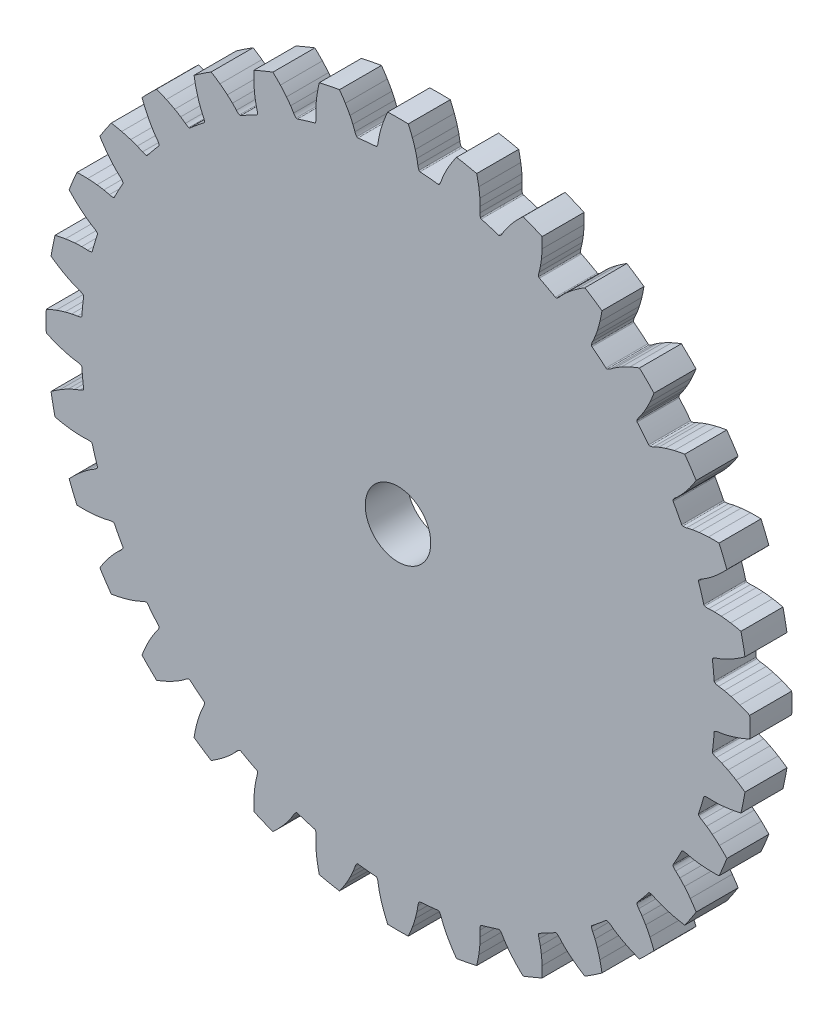
SolidWorks part; units mm, degrees
material "ASTM A36 Steel"
ref_plane "Front Plane" through (0, 0, 0) normal (0, 0, 1) x (1, 0, 0)
ref_plane "Top Plane" through (0, 0, 0) normal (0, 1, 0) x (1, 0, 0)
ref_plane "Right Plane" through (0, 0, 0) normal (1, 0, 0) x (0, 0, -1)
sketch "Model" plane through (0, 0, 0) normal (0, 0, 1) x (1, 0, 0)
  arc A1 (47.6887, -4.6969) -> (47.803, -3.3385) centre (0, 0) ccw
  arc A2 (47.9144, -3.1714) -> (47.803, -3.3385) centre (48.0052, -3.3526) ccw
  arc A3 (48.4758, -3.0015) -> (47.9144, -3.1714) centre (48.6888, -4.7173) ccw
  arc A4 (48.4758, -3.0015) -> (49.3301, -2.859) centre (47.1969, 7.2969) ccw
  arc A5 (49.3301, -2.859) -> (50.3502, -2.6078) centre (46.1914, 12.0843) ccw
  arc A6 (50.3502, -2.6078) -> (51.6994, -2.1663) centre (45.5635, 14.3022) ccw
  arc A7 (51.6994, -2.1663) -> (53.1817, -1.5528) centre (43.8651, 18.8607) ccw
  arc A8 (53.1817, -1.5528) -> (53.1817, 1.5528) centre (0, 0) ccw
  arc A9 (53.1817, 1.5528) -> (51.6994, 2.1663) centre (43.8651, -18.8607) ccw
  arc A10 (51.6994, 2.1663) -> (50.3502, 2.6078) centre (45.5635, -14.3022) ccw
  arc A11 (50.3502, 2.6078) -> (49.3301, 2.859) centre (46.1914, -12.0843) ccw
  arc A12 (49.3301, 2.859) -> (48.4758, 3.0015) centre (47.1969, -7.2969) ccw
  arc A13 (47.9144, 3.1714) -> (48.4758, 3.0015) centre (48.6888, 4.7173) ccw
  arc A14 (47.803, 3.3385) -> (47.9144, 3.1714) centre (48.0052, 3.3526) ccw
  arc A15 (47.803, 3.3385) -> (47.5358, 6.0515) centre (0, 0) ccw
  arc A16 (47.6124, 6.2371) -> (47.5358, 6.0515) centre (47.7368, 6.0771) ccw
  arc A17 (48.1299, 6.5133) -> (47.6124, 6.2371) centre (48.6736, 4.872) ccw
  arc A18 (48.1299, 6.5133) -> (48.94, 6.8198) centre (44.8665, 16.3643) ccw
  arc A19 (48.94, 6.8198) -> (49.8915, 7.2652) centre (42.9463, 20.8636) ccw
  arc A20 (49.8915, 7.2652) -> (51.1287, 7.9614) centre (41.8978, 22.9164) ccw
  arc A21 (51.1287, 7.9614) -> (52.4627, 8.8522) centre (39.3427, 27.056) ccw
  arc A22 (52.4627, 8.8522) -> (51.8568, 11.8982) centre (0, 0) ccw
  arc A23 (51.8568, 11.8982) -> (50.2834, 12.2107) centre (46.7018, -9.9407) ccw
  arc A24 (50.2834, 12.2107) -> (48.874, 12.3805) centre (47.4783, -5.1384) ccw
  arc A25 (48.874, 12.3805) -> (47.8244, 12.4279) centre (47.6613, -2.8406) ccw
  arc A26 (47.8244, 12.4279) -> (46.9587, 12.401) centre (47.7136, 2.051) ccw
  arc A27 (46.375, 12.4581) -> (46.9587, 12.401) centre (46.833, 14.1254) ccw
  arc A28 (46.2332, 12.6003) -> (46.375, 12.4581) centre (46.4287, 12.6536) ccw
  arc A29 (46.2332, 12.6003) -> (45.4418, 15.209) centre (0, 0) ccw
  arc A30 (45.4808, 15.406) -> (45.4418, 15.209) centre (45.634, 15.2733) ccw
  arc A31 (45.9344, 15.7779) -> (45.4808, 15.406) centre (46.7879, 14.2741) ccw
  arc A32 (45.9344, 15.7779) -> (46.6691, 16.2364) centre (40.8119, 24.8029) ccw
  arc A33 (46.6691, 16.2364) -> (47.5155, 16.8589) centre (38.0508, 28.8411) ccw
  arc A34 (47.5155, 16.8589) -> (48.5931, 17.7832) centre (36.622, 30.6499) ccw
  arc A35 (48.5931, 17.7832) -> (49.7277, 18.9171) centre (33.3084, 34.2115) ccw
  arc A36 (49.7277, 18.9171) -> (48.5392, 21.7864) centre (0, 0) ccw
  arc A37 (48.5392, 21.7864) -> (46.9351, 21.7859) centre (47.7438, -0.6386) ccw
  arc A38 (46.9351, 21.7859) -> (45.5196, 21.6775) centre (47.5684, 4.2229) ccw
  arc A39 (45.5196, 21.6775) -> (44.481, 21.5192) centre (47.2997, 6.5122) ccw
  arc A40 (44.481, 21.5192) -> (43.6371, 21.3239) centre (46.3967, 11.3201) ccw
  arc A41 (43.0535, 21.2661) -> (43.6371, 21.3239) centre (43.1774, 22.9907) ccw
  arc A42 (42.8866, 21.3778) -> (43.0535, 21.2661) centre (43.068, 21.4682) ccw
  arc A43 (42.8866, 21.3778) -> (41.6015, 23.782) centre (0, 0) ccw
  arc A44 (41.6013, 23.9828) -> (41.6015, 23.782) centre (41.7775, 23.8826) ccw
  arc A45 (41.9737, 24.436) -> (41.6013, 23.9828) centre (43.1041, 23.1277) ccw
  arc A46 (41.9737, 24.436) -> (42.6048, 25.0292) centre (35.1889, 32.2883) ccw
  arc A47 (42.6048, 25.0292) -> (43.3135, 25.8048) centre (31.693, 35.7103) ccw
  arc A48 (43.3135, 25.8048) -> (44.19, 26.9215) centre (29.9388, 37.2056) ccw
  arc A49 (44.19, 26.9215) -> (45.0816, 28.255) centre (25.994, 40.0523) ccw
  arc A50 (45.0816, 28.255) -> (43.3562, 30.8373) centre (0, 0) ccw
  arc A51 (43.3562, 30.8373) -> (41.783, 30.5239) centre (46.951, 8.688) ccw
  arc A52 (41.783, 30.5239) -> (40.4159, 30.1414) centre (45.8306, 13.4219) ccw
  arc A53 (40.4159, 30.1414) -> (39.4281, 29.7835) centre (45.1204, 15.6148) ccw
  arc A54 (39.4281, 29.7835) -> (38.6386, 29.4273) centre (43.2967, 20.1541) ccw
  arc A55 (38.0774, 29.2568) -> (38.6386, 29.4273) centre (37.8625, 30.9724) ccw
  arc A56 (37.892, 29.3338) -> (38.0774, 29.2568) centre (38.0522, 29.4579) ccw
  arc A57 (37.892, 29.3338) -> (36.1625, 31.4411) centre (0, 0) ccw
  arc A58 (36.1231, 31.638) -> (36.1625, 31.4411) centre (36.3154, 31.5741) ccw
  arc A59 (36.3999, 32.1552) -> (36.1231, 31.638) centre (37.7639, 31.0925) ccw
  arc A60 (36.3999, 32.1552) -> (36.9032, 32.86) centre (28.2136, 38.5329) ccw
  arc A61 (36.9032, 32.86) -> (37.447, 33.759) centre (24.1173, 41.2071) ccw
  arc A62 (37.447, 33.759) -> (38.0888, 35.0253) centre (22.1051, 42.3315) ccw
  arc A63 (38.0888, 35.0253) -> (38.7031, 36.5071) centre (17.6808, 44.3539) ccw
  arc A64 (38.7031, 36.5071) -> (36.5071, 38.7031) centre (0, 0) ccw
  arc A65 (36.5071, 38.7031) -> (35.0253, 38.0888) centre (44.3539, 17.6808) ccw
  arc A66 (35.0253, 38.0888) -> (33.759, 37.447) centre (42.3315, 22.1051) ccw
  arc A67 (33.759, 37.447) -> (32.86, 36.9032) centre (41.2071, 24.1173) ccw
  arc A68 (32.86, 36.9032) -> (32.1552, 36.3999) centre (38.5329, 28.2136) ccw
  arc A69 (31.638, 36.1231) -> (32.1552, 36.3999) centre (31.0925, 37.7639) ccw
  arc A70 (31.4411, 36.1625) -> (31.638, 36.1231) centre (31.5741, 36.3154) ccw
  arc A71 (31.4411, 36.1625) -> (29.3338, 37.892) centre (0, 0) ccw
  arc A72 (29.2568, 38.0774) -> (29.3338, 37.892) centre (29.4579, 38.0522) ccw
  arc A73 (29.4273, 38.6386) -> (29.2568, 38.0774) centre (30.9724, 37.8625) ccw
  arc A74 (29.4273, 38.6386) -> (29.7835, 39.4281) centre (20.1541, 43.2967) ccw
  arc A75 (29.7835, 39.4281) -> (30.1414, 40.4159) centre (15.6148, 45.1204) ccw
  arc A76 (30.1414, 40.4159) -> (30.5239, 41.783) centre (13.4219, 45.8306) ccw
  arc A77 (30.5239, 41.783) -> (30.8373, 43.3562) centre (8.688, 46.951) ccw
  arc A78 (30.8373, 43.3562) -> (28.255, 45.0816) centre (0, 0) ccw
  arc A79 (28.255, 45.0816) -> (26.9215, 44.19) centre (40.0523, 25.994) ccw
  arc A80 (26.9215, 44.19) -> (25.8048, 43.3135) centre (37.2056, 29.9388) ccw
  arc A81 (25.8048, 43.3135) -> (25.0292, 42.6048) centre (35.7103, 31.693) ccw
  arc A82 (25.0292, 42.6048) -> (24.436, 41.9737) centre (32.2883, 35.1889) ccw
  arc A83 (23.9828, 41.6013) -> (24.436, 41.9737) centre (23.1277, 43.1041) ccw
  arc A84 (23.782, 41.6015) -> (23.9828, 41.6013) centre (23.8826, 41.7775) ccw
  arc A85 (23.782, 41.6015) -> (21.3778, 42.8866) centre (0, 0) ccw
  arc A86 (21.2661, 43.0535) -> (21.3778, 42.8866) centre (21.4682, 43.068) ccw
  arc A87 (21.3239, 43.6371) -> (21.2661, 43.0535) centre (22.9907, 43.1774) ccw
  arc A88 (21.3239, 43.6371) -> (21.5192, 44.481) centre (11.3201, 46.3967) ccw
  arc A89 (21.5192, 44.481) -> (21.6775, 45.5196) centre (6.5122, 47.2997) ccw
  arc A90 (21.6775, 45.5196) -> (21.7859, 46.9351) centre (4.2229, 47.5684) ccw
  arc A91 (21.7859, 46.9351) -> (21.7864, 48.5392) centre (-0.6386, 47.7438) ccw
  arc A92 (21.7864, 48.5392) -> (18.9171, 49.7277) centre (0, 0) ccw
  arc A93 (18.9171, 49.7277) -> (17.7832, 48.5931) centre (34.2115, 33.3084) ccw
  arc A94 (17.7832, 48.5931) -> (16.8589, 47.5155) centre (30.6499, 36.622) ccw
  arc A95 (16.8589, 47.5155) -> (16.2364, 46.6691) centre (28.8411, 38.0508) ccw
  arc A96 (16.2364, 46.6691) -> (15.7779, 45.9344) centre (24.8029, 40.8119) ccw
  arc A97 (15.406, 45.4808) -> (15.7779, 45.9344) centre (14.2741, 46.7879) ccw
  arc A98 (15.209, 45.4418) -> (15.406, 45.4808) centre (15.2733, 45.634) ccw
  arc A99 (15.209, 45.4418) -> (12.6003, 46.2332) centre (0, 0) ccw
  arc A100 (12.4581, 46.375) -> (12.6003, 46.2332) centre (12.6536, 46.4287) ccw
  arc A101 (12.401, 46.9587) -> (12.4581, 46.375) centre (14.1254, 46.833) ccw
  arc A102 (12.401, 46.9587) -> (12.4279, 47.8244) centre (2.051, 47.7136) ccw
  arc A103 (12.4279, 47.8244) -> (12.3805, 48.874) centre (-2.8406, 47.6613) ccw
  arc A104 (12.3805, 48.874) -> (12.2107, 50.2834) centre (-5.1384, 47.4783) ccw
  arc A105 (12.2107, 50.2834) -> (11.8982, 51.8568) centre (-9.9407, 46.7018) ccw
  arc A106 (11.8982, 51.8568) -> (8.8522, 52.4627) centre (0, 0) ccw
  arc A107 (8.8522, 52.4627) -> (7.9614, 51.1287) centre (27.056, 39.3427) ccw
  arc A108 (7.9614, 51.1287) -> (7.2652, 49.8915) centre (22.9164, 41.8978) ccw
  arc A109 (7.2652, 49.8915) -> (6.8198, 48.94) centre (20.8636, 42.9463) ccw
  arc A110 (6.8198, 48.94) -> (6.5133, 48.1299) centre (16.3643, 44.8665) ccw
  arc A111 (6.2371, 47.6124) -> (6.5133, 48.1299) centre (4.872, 48.6736) ccw
  arc A112 (6.0515, 47.5358) -> (6.2371, 47.6124) centre (6.0771, 47.7368) ccw
  arc A113 (6.0515, 47.5358) -> (3.3385, 47.803) centre (0, 0) ccw
  arc A114 (3.1714, 47.9144) -> (3.3385, 47.803) centre (3.3526, 48.0052) ccw
  arc A115 (3.0015, 48.4758) -> (3.1714, 47.9144) centre (4.7173, 48.6888) ccw
  arc A116 (3.0015, 48.4758) -> (2.859, 49.3301) centre (-7.2969, 47.1969) ccw
  arc A117 (2.859, 49.3301) -> (2.6078, 50.3502) centre (-12.0843, 46.1914) ccw
  arc A118 (2.6078, 50.3502) -> (2.1663, 51.6994) centre (-14.3022, 45.5635) ccw
  arc A119 (2.1663, 51.6994) -> (1.5528, 53.1817) centre (-18.8607, 43.8651) ccw
  arc A120 (1.5528, 53.1817) -> (-1.5528, 53.1817) centre (0, 0) ccw
  arc A121 (-1.5528, 53.1817) -> (-2.1663, 51.6994) centre (18.8607, 43.8651) ccw
  arc A122 (-2.1663, 51.6994) -> (-2.6078, 50.3502) centre (14.3022, 45.5635) ccw
  arc A123 (-2.6078, 50.3502) -> (-2.859, 49.3301) centre (12.0843, 46.1914) ccw
  arc A124 (-2.859, 49.3301) -> (-3.0015, 48.4758) centre (7.2969, 47.1969) ccw
  arc A125 (-3.1714, 47.9144) -> (-3.0015, 48.4758) centre (-4.7173, 48.6888) ccw
  arc A126 (-3.3385, 47.803) -> (-3.1714, 47.9144) centre (-3.3526, 48.0052) ccw
  arc A127 (-3.3385, 47.803) -> (-6.0515, 47.5358) centre (0, 0) ccw
  arc A128 (-6.2371, 47.6124) -> (-6.0515, 47.5358) centre (-6.0771, 47.7368) ccw
  arc A129 (-6.5133, 48.1299) -> (-6.2371, 47.6124) centre (-4.872, 48.6736) ccw
  arc A130 (-6.5133, 48.1299) -> (-6.8198, 48.94) centre (-16.3643, 44.8665) ccw
  arc A131 (-6.8198, 48.94) -> (-7.2652, 49.8915) centre (-20.8636, 42.9463) ccw
  arc A132 (-7.2652, 49.8915) -> (-7.9614, 51.1287) centre (-22.9164, 41.8978) ccw
  arc A133 (-7.9614, 51.1287) -> (-8.8522, 52.4627) centre (-27.056, 39.3427) ccw
  arc A134 (-8.8522, 52.4627) -> (-11.8982, 51.8568) centre (0, 0) ccw
  arc A135 (-11.8982, 51.8568) -> (-12.2107, 50.2834) centre (9.9407, 46.7018) ccw
  arc A136 (-12.2107, 50.2834) -> (-12.3805, 48.874) centre (5.1384, 47.4783) ccw
  arc A137 (-12.3805, 48.874) -> (-12.4279, 47.8244) centre (2.8406, 47.6613) ccw
  arc A138 (-12.4279, 47.8244) -> (-12.401, 46.9587) centre (-2.051, 47.7136) ccw
  arc A139 (-12.4581, 46.375) -> (-12.401, 46.9587) centre (-14.1254, 46.833) ccw
  arc A140 (-12.6003, 46.2332) -> (-12.4581, 46.375) centre (-12.6536, 46.4287) ccw
  arc A141 (-12.6003, 46.2332) -> (-15.209, 45.4418) centre (0, 0) ccw
  arc A142 (-15.406, 45.4808) -> (-15.209, 45.4418) centre (-15.2733, 45.634) ccw
  arc A143 (-15.7779, 45.9344) -> (-15.406, 45.4808) centre (-14.2741, 46.7879) ccw
  arc A144 (-15.7779, 45.9344) -> (-16.2364, 46.6691) centre (-24.8029, 40.8119) ccw
  arc A145 (-16.2364, 46.6691) -> (-16.8589, 47.5155) centre (-28.8411, 38.0508) ccw
  arc A146 (-16.8589, 47.5155) -> (-17.7832, 48.5931) centre (-30.6499, 36.622) ccw
  arc A147 (-17.7832, 48.5931) -> (-18.9171, 49.7277) centre (-34.2115, 33.3084) ccw
  arc A148 (-18.9171, 49.7277) -> (-21.7864, 48.5392) centre (0, 0) ccw
  arc A149 (-21.7864, 48.5392) -> (-21.7859, 46.9351) centre (0.6386, 47.7438) ccw
  arc A150 (-21.7859, 46.9351) -> (-21.6775, 45.5196) centre (-4.2229, 47.5684) ccw
  arc A151 (-21.6775, 45.5196) -> (-21.5192, 44.481) centre (-6.5122, 47.2997) ccw
  arc A152 (-21.5192, 44.481) -> (-21.3239, 43.6371) centre (-11.3201, 46.3967) ccw
  arc A153 (-21.2661, 43.0535) -> (-21.3239, 43.6371) centre (-22.9907, 43.1774) ccw
  arc A154 (-21.3778, 42.8866) -> (-21.2661, 43.0535) centre (-21.4682, 43.068) ccw
  arc A155 (-21.3778, 42.8866) -> (-23.782, 41.6015) centre (0, 0) ccw
  arc A156 (-23.9828, 41.6013) -> (-23.782, 41.6015) centre (-23.8826, 41.7775) ccw
  arc A157 (-24.436, 41.9737) -> (-23.9828, 41.6013) centre (-23.1277, 43.1041) ccw
  arc A158 (-24.436, 41.9737) -> (-25.0292, 42.6048) centre (-32.2883, 35.1889) ccw
  arc A159 (-25.0292, 42.6048) -> (-25.8048, 43.3135) centre (-35.7103, 31.693) ccw
  arc A160 (-25.8048, 43.3135) -> (-26.9215, 44.19) centre (-37.2056, 29.9388) ccw
  arc A161 (-26.9215, 44.19) -> (-28.255, 45.0816) centre (-40.0523, 25.994) ccw
  arc A162 (-28.255, 45.0816) -> (-30.8373, 43.3562) centre (0, 0) ccw
  arc A163 (-30.8373, 43.3562) -> (-30.5239, 41.783) centre (-8.688, 46.951) ccw
  arc A164 (-30.5239, 41.783) -> (-30.1414, 40.4159) centre (-13.4219, 45.8306) ccw
  arc A165 (-30.1414, 40.4159) -> (-29.7835, 39.4281) centre (-15.6148, 45.1204) ccw
  arc A166 (-29.7835, 39.4281) -> (-29.4273, 38.6386) centre (-20.1541, 43.2967) ccw
  arc A167 (-29.2568, 38.0774) -> (-29.4273, 38.6386) centre (-30.9724, 37.8625) ccw
  arc A168 (-29.3338, 37.892) -> (-29.2568, 38.0774) centre (-29.4579, 38.0522) ccw
  arc A169 (-29.3338, 37.892) -> (-31.4411, 36.1625) centre (0, 0) ccw
  arc A170 (-31.638, 36.1231) -> (-31.4411, 36.1625) centre (-31.5741, 36.3154) ccw
  arc A171 (-32.1552, 36.3999) -> (-31.638, 36.1231) centre (-31.0925, 37.7639) ccw
  arc A172 (-32.1552, 36.3999) -> (-32.86, 36.9032) centre (-38.5329, 28.2136) ccw
  arc A173 (-32.86, 36.9032) -> (-33.759, 37.447) centre (-41.2071, 24.1173) ccw
  arc A174 (-33.759, 37.447) -> (-35.0253, 38.0888) centre (-42.3315, 22.1051) ccw
  arc A175 (-35.0253, 38.0888) -> (-36.5071, 38.7031) centre (-44.3539, 17.6808) ccw
  arc A176 (-36.5071, 38.7031) -> (-38.7031, 36.5071) centre (0, 0) ccw
  arc A177 (-38.7031, 36.5071) -> (-38.0888, 35.0253) centre (-17.6808, 44.3539) ccw
  arc A178 (-38.0888, 35.0253) -> (-37.447, 33.759) centre (-22.1051, 42.3315) ccw
  arc A179 (-37.447, 33.759) -> (-36.9032, 32.86) centre (-24.1173, 41.2071) ccw
  arc A180 (-36.9032, 32.86) -> (-36.3999, 32.1552) centre (-28.2136, 38.5329) ccw
  arc A181 (-36.1231, 31.638) -> (-36.3999, 32.1552) centre (-37.7639, 31.0925) ccw
  arc A182 (-36.1625, 31.4411) -> (-36.1231, 31.638) centre (-36.3154, 31.5741) ccw
  arc A183 (-36.1625, 31.4411) -> (-37.892, 29.3338) centre (0, 0) ccw
  arc A184 (-38.0774, 29.2568) -> (-37.892, 29.3338) centre (-38.0522, 29.4579) ccw
  arc A185 (-38.6386, 29.4273) -> (-38.0774, 29.2568) centre (-37.8625, 30.9724) ccw
  arc A186 (-38.6386, 29.4273) -> (-39.4281, 29.7835) centre (-43.2967, 20.1541) ccw
  arc A187 (-39.4281, 29.7835) -> (-40.4159, 30.1414) centre (-45.1204, 15.6148) ccw
  arc A188 (-40.4159, 30.1414) -> (-41.783, 30.5239) centre (-45.8306, 13.4219) ccw
  arc A189 (-41.783, 30.5239) -> (-43.3562, 30.8373) centre (-46.951, 8.688) ccw
  arc A190 (-43.3562, 30.8373) -> (-45.0816, 28.255) centre (0, 0) ccw
  arc A191 (-45.0816, 28.255) -> (-44.19, 26.9215) centre (-25.994, 40.0523) ccw
  arc A192 (-44.19, 26.9215) -> (-43.3135, 25.8048) centre (-29.9388, 37.2056) ccw
  arc A193 (-43.3135, 25.8048) -> (-42.6048, 25.0292) centre (-31.693, 35.7103) ccw
  arc A194 (-42.6048, 25.0292) -> (-41.9737, 24.436) centre (-35.1889, 32.2883) ccw
  arc A195 (-41.6013, 23.9828) -> (-41.9737, 24.436) centre (-43.1041, 23.1277) ccw
  arc A196 (-41.6015, 23.782) -> (-41.6013, 23.9828) centre (-41.7775, 23.8826) ccw
  arc A197 (-41.6015, 23.782) -> (-42.8866, 21.3778) centre (0, 0) ccw
  arc A198 (-43.0535, 21.2661) -> (-42.8866, 21.3778) centre (-43.068, 21.4682) ccw
  arc A199 (-43.6371, 21.3239) -> (-43.0535, 21.2661) centre (-43.1774, 22.9907) ccw
  arc A200 (-43.6371, 21.3239) -> (-44.481, 21.5192) centre (-46.3967, 11.3201) ccw
  arc A201 (-44.481, 21.5192) -> (-45.5196, 21.6775) centre (-47.2997, 6.5122) ccw
  arc A202 (-45.5196, 21.6775) -> (-46.9351, 21.7859) centre (-47.5684, 4.2229) ccw
  arc A203 (-46.9351, 21.7859) -> (-48.5392, 21.7864) centre (-47.7438, -0.6386) ccw
  arc A204 (-48.5392, 21.7864) -> (-49.7277, 18.9171) centre (0, 0) ccw
  arc A205 (-49.7277, 18.9171) -> (-48.5931, 17.7832) centre (-33.3084, 34.2115) ccw
  arc A206 (-48.5931, 17.7832) -> (-47.5155, 16.8589) centre (-36.622, 30.6499) ccw
  arc A207 (-47.5155, 16.8589) -> (-46.6691, 16.2364) centre (-38.0508, 28.8411) ccw
  arc A208 (-46.6691, 16.2364) -> (-45.9344, 15.7779) centre (-40.8119, 24.8029) ccw
  arc A209 (-45.4808, 15.406) -> (-45.9344, 15.7779) centre (-46.7879, 14.2741) ccw
  arc A210 (-45.4418, 15.209) -> (-45.4808, 15.406) centre (-45.634, 15.2733) ccw
  arc A211 (-45.4418, 15.209) -> (-46.2332, 12.6003) centre (0, 0) ccw
  arc A212 (-46.375, 12.4581) -> (-46.2332, 12.6003) centre (-46.4287, 12.6536) ccw
  arc A213 (-46.9587, 12.401) -> (-46.375, 12.4581) centre (-46.833, 14.1254) ccw
  arc A214 (-46.9587, 12.401) -> (-47.8244, 12.4279) centre (-47.7136, 2.051) ccw
  arc A215 (-47.8244, 12.4279) -> (-48.874, 12.3805) centre (-47.6613, -2.8406) ccw
  arc A216 (-48.874, 12.3805) -> (-50.2834, 12.2107) centre (-47.4783, -5.1384) ccw
  arc A217 (-50.2834, 12.2107) -> (-51.8568, 11.8982) centre (-46.7018, -9.9407) ccw
  arc A218 (-51.8568, 11.8982) -> (-52.4627, 8.8522) centre (0, 0) ccw
  arc A219 (-52.4627, 8.8522) -> (-51.1287, 7.9614) centre (-39.3427, 27.056) ccw
  arc A220 (-51.1287, 7.9614) -> (-49.8915, 7.2652) centre (-41.8978, 22.9164) ccw
  arc A221 (-49.8915, 7.2652) -> (-48.94, 6.8198) centre (-42.9463, 20.8636) ccw
  arc A222 (-48.94, 6.8198) -> (-48.1299, 6.5133) centre (-44.8665, 16.3643) ccw
  arc A223 (-47.6124, 6.2371) -> (-48.1299, 6.5133) centre (-48.6736, 4.872) ccw
  arc A224 (-47.5358, 6.0515) -> (-47.6124, 6.2371) centre (-47.7368, 6.0771) ccw
  arc A225 (-47.5358, 6.0515) -> (-47.803, 3.3385) centre (0, 0) ccw
  arc A226 (-47.9144, 3.1714) -> (-47.803, 3.3385) centre (-48.0052, 3.3526) ccw
  arc A227 (-48.4758, 3.0015) -> (-47.9144, 3.1714) centre (-48.6888, 4.7173) ccw
  arc A228 (-48.4758, 3.0015) -> (-49.3301, 2.859) centre (-47.1969, -7.2969) ccw
  arc A229 (-49.3301, 2.859) -> (-50.3502, 2.6078) centre (-46.1914, -12.0843) ccw
  arc A230 (-50.3502, 2.6078) -> (-51.6994, 2.1663) centre (-45.5635, -14.3022) ccw
  arc A231 (-51.6994, 2.1663) -> (-53.1817, 1.5528) centre (-43.8651, -18.8607) ccw
  arc A232 (-53.1817, 1.5528) -> (-53.1817, -1.5528) centre (0, 0) ccw
  arc A233 (-53.1817, -1.5528) -> (-51.6994, -2.1663) centre (-43.8651, 18.8607) ccw
  arc A234 (-51.6994, -2.1663) -> (-50.3502, -2.6078) centre (-45.5635, 14.3022) ccw
  arc A235 (-50.3502, -2.6078) -> (-49.3301, -2.859) centre (-46.1914, 12.0843) ccw
  arc A236 (-49.3301, -2.859) -> (-48.4758, -3.0015) centre (-47.1969, 7.2969) ccw
  arc A237 (-47.9144, -3.1714) -> (-48.4758, -3.0015) centre (-48.6888, -4.7173) ccw
  arc A238 (-47.803, -3.3385) -> (-47.9144, -3.1714) centre (-48.0052, -3.3526) ccw
  arc A239 (-47.803, -3.3385) -> (-47.5358, -6.0515) centre (0, 0) ccw
  arc A240 (-47.6124, -6.2371) -> (-47.5358, -6.0515) centre (-47.7368, -6.0771) ccw
  arc A241 (-48.1299, -6.5133) -> (-47.6124, -6.2371) centre (-48.6736, -4.872) ccw
  arc A242 (-48.1299, -6.5133) -> (-48.94, -6.8198) centre (-44.8665, -16.3643) ccw
  arc A243 (-48.94, -6.8198) -> (-49.8915, -7.2652) centre (-42.9463, -20.8636) ccw
  arc A244 (-49.8915, -7.2652) -> (-51.1287, -7.9614) centre (-41.8978, -22.9164) ccw
  arc A245 (-51.1287, -7.9614) -> (-52.4627, -8.8522) centre (-39.3427, -27.056) ccw
  arc A246 (-52.4627, -8.8522) -> (-51.8568, -11.8982) centre (0, 0) ccw
  arc A247 (-51.8568, -11.8982) -> (-50.2834, -12.2107) centre (-46.7018, 9.9407) ccw
  arc A248 (-50.2834, -12.2107) -> (-48.874, -12.3805) centre (-47.4783, 5.1384) ccw
  arc A249 (-48.874, -12.3805) -> (-47.8244, -12.4279) centre (-47.6613, 2.8406) ccw
  arc A250 (-47.8244, -12.4279) -> (-46.9587, -12.401) centre (-47.7136, -2.051) ccw
  arc A251 (-46.375, -12.4581) -> (-46.9587, -12.401) centre (-46.833, -14.1254) ccw
  arc A252 (-46.2332, -12.6003) -> (-46.375, -12.4581) centre (-46.4287, -12.6536) ccw
  arc A253 (-46.2332, -12.6003) -> (-45.4418, -15.209) centre (0, 0) ccw
  arc A254 (-45.4808, -15.406) -> (-45.4418, -15.209) centre (-45.634, -15.2733) ccw
  arc A255 (-45.9344, -15.7779) -> (-45.4808, -15.406) centre (-46.7879, -14.2741) ccw
  arc A256 (-45.9344, -15.7779) -> (-46.6691, -16.2364) centre (-40.8119, -24.8029) ccw
  arc A257 (-46.6691, -16.2364) -> (-47.5155, -16.8589) centre (-38.0508, -28.8411) ccw
  arc A258 (-47.5155, -16.8589) -> (-48.5931, -17.7832) centre (-36.622, -30.6499) ccw
  arc A259 (-48.5931, -17.7832) -> (-49.7277, -18.9171) centre (-33.3084, -34.2115) ccw
  arc A260 (-49.7277, -18.9171) -> (-48.5392, -21.7864) centre (0, 0) ccw
  arc A261 (-48.5392, -21.7864) -> (-46.9351, -21.7859) centre (-47.7438, 0.6386) ccw
  arc A262 (-46.9351, -21.7859) -> (-45.5196, -21.6775) centre (-47.5684, -4.2229) ccw
  arc A263 (-45.5196, -21.6775) -> (-44.481, -21.5192) centre (-47.2997, -6.5122) ccw
  arc A264 (-44.481, -21.5192) -> (-43.6371, -21.3239) centre (-46.3967, -11.3201) ccw
  arc A265 (-43.0535, -21.2661) -> (-43.6371, -21.3239) centre (-43.1774, -22.9907) ccw
  arc A266 (-42.8866, -21.3778) -> (-43.0535, -21.2661) centre (-43.068, -21.4682) ccw
  arc A267 (-42.8866, -21.3778) -> (-41.6015, -23.782) centre (0, 0) ccw
  arc A268 (-41.6013, -23.9828) -> (-41.6015, -23.782) centre (-41.7775, -23.8826) ccw
  arc A269 (-41.9737, -24.436) -> (-41.6013, -23.9828) centre (-43.1041, -23.1277) ccw
  arc A270 (-41.9737, -24.436) -> (-42.6048, -25.0292) centre (-35.1889, -32.2883) ccw
  arc A271 (-42.6048, -25.0292) -> (-43.3135, -25.8048) centre (-31.693, -35.7103) ccw
  arc A272 (-43.3135, -25.8048) -> (-44.19, -26.9215) centre (-29.9388, -37.2056) ccw
  arc A273 (-44.19, -26.9215) -> (-45.0816, -28.255) centre (-25.994, -40.0523) ccw
  arc A274 (-45.0816, -28.255) -> (-43.3562, -30.8373) centre (0, 0) ccw
  arc A275 (-43.3562, -30.8373) -> (-41.783, -30.5239) centre (-46.951, -8.688) ccw
  arc A276 (-41.783, -30.5239) -> (-40.4159, -30.1414) centre (-45.8306, -13.4219) ccw
  arc A277 (-40.4159, -30.1414) -> (-39.4281, -29.7835) centre (-45.1204, -15.6148) ccw
  arc A278 (-39.4281, -29.7835) -> (-38.6386, -29.4273) centre (-43.2967, -20.1541) ccw
  arc A279 (-38.0774, -29.2568) -> (-38.6386, -29.4273) centre (-37.8625, -30.9724) ccw
  arc A280 (-37.892, -29.3338) -> (-38.0774, -29.2568) centre (-38.0522, -29.4579) ccw
  arc A281 (-37.892, -29.3338) -> (-36.1625, -31.4411) centre (0, 0) ccw
  arc A282 (-36.1231, -31.638) -> (-36.1625, -31.4411) centre (-36.3154, -31.5741) ccw
  arc A283 (-36.3999, -32.1552) -> (-36.1231, -31.638) centre (-37.7639, -31.0925) ccw
  arc A284 (-36.3999, -32.1552) -> (-36.9032, -32.86) centre (-28.2136, -38.5329) ccw
  arc A285 (-36.9032, -32.86) -> (-37.447, -33.759) centre (-24.1173, -41.2071) ccw
  arc A286 (-37.447, -33.759) -> (-38.0888, -35.0253) centre (-22.1051, -42.3315) ccw
  arc A287 (-38.0888, -35.0253) -> (-38.7031, -36.5071) centre (-17.6808, -44.3539) ccw
  arc A288 (-38.7031, -36.5071) -> (-36.5071, -38.7031) centre (0, 0) ccw
  arc A289 (-36.5071, -38.7031) -> (-35.0253, -38.0888) centre (-44.3539, -17.6808) ccw
  arc A290 (-35.0253, -38.0888) -> (-33.759, -37.447) centre (-42.3315, -22.1051) ccw
  arc A291 (-33.759, -37.447) -> (-32.86, -36.9032) centre (-41.2071, -24.1173) ccw
  arc A292 (-32.86, -36.9032) -> (-32.1552, -36.3999) centre (-38.5329, -28.2136) ccw
  arc A293 (-31.638, -36.1231) -> (-32.1552, -36.3999) centre (-31.0925, -37.7639) ccw
  arc A294 (-31.4411, -36.1625) -> (-31.638, -36.1231) centre (-31.5741, -36.3154) ccw
  arc A295 (-31.4411, -36.1625) -> (-29.3338, -37.892) centre (0, 0) ccw
  arc A296 (-29.2568, -38.0774) -> (-29.3338, -37.892) centre (-29.4579, -38.0522) ccw
  arc A297 (-29.4273, -38.6386) -> (-29.2568, -38.0774) centre (-30.9724, -37.8625) ccw
  arc A298 (-29.4273, -38.6386) -> (-29.7835, -39.4281) centre (-20.1541, -43.2967) ccw
  arc A299 (-29.7835, -39.4281) -> (-30.1414, -40.4159) centre (-15.6148, -45.1204) ccw
  arc A300 (-30.1414, -40.4159) -> (-30.5239, -41.783) centre (-13.4219, -45.8306) ccw
  arc A301 (-30.5239, -41.783) -> (-30.8373, -43.3562) centre (-8.688, -46.951) ccw
  arc A302 (-30.8373, -43.3562) -> (-28.255, -45.0816) centre (0, 0) ccw
  arc A303 (-28.255, -45.0816) -> (-26.9215, -44.19) centre (-40.0523, -25.994) ccw
  arc A304 (-26.9215, -44.19) -> (-25.8048, -43.3135) centre (-37.2056, -29.9388) ccw
  arc A305 (-25.8048, -43.3135) -> (-25.0292, -42.6048) centre (-35.7103, -31.693) ccw
  arc A306 (-25.0292, -42.6048) -> (-24.436, -41.9737) centre (-32.2883, -35.1889) ccw
  arc A307 (-23.9828, -41.6013) -> (-24.436, -41.9737) centre (-23.1277, -43.1041) ccw
  arc A308 (-23.782, -41.6015) -> (-23.9828, -41.6013) centre (-23.8826, -41.7775) ccw
  arc A309 (-23.782, -41.6015) -> (-21.3778, -42.8866) centre (0, 0) ccw
  arc A310 (-21.2661, -43.0535) -> (-21.3778, -42.8866) centre (-21.4682, -43.068) ccw
  arc A311 (-21.3239, -43.6371) -> (-21.2661, -43.0535) centre (-22.9907, -43.1774) ccw
  arc A312 (-21.3239, -43.6371) -> (-21.5192, -44.481) centre (-11.3201, -46.3967) ccw
  arc A313 (-21.5192, -44.481) -> (-21.6775, -45.5196) centre (-6.5122, -47.2997) ccw
  arc A314 (-21.6775, -45.5196) -> (-21.7859, -46.9351) centre (-4.2229, -47.5684) ccw
  arc A315 (-21.7859, -46.9351) -> (-21.7864, -48.5392) centre (0.6386, -47.7438) ccw
  arc A316 (-21.7864, -48.5392) -> (-18.9171, -49.7277) centre (0, 0) ccw
  arc A317 (-18.9171, -49.7277) -> (-17.7832, -48.5931) centre (-34.2115, -33.3084) ccw
  arc A318 (-17.7832, -48.5931) -> (-16.8589, -47.5155) centre (-30.6499, -36.622) ccw
  arc A319 (-16.8589, -47.5155) -> (-16.2364, -46.6691) centre (-28.8411, -38.0508) ccw
  arc A320 (-16.2364, -46.6691) -> (-15.7779, -45.9344) centre (-24.8029, -40.8119) ccw
  arc A321 (-15.406, -45.4808) -> (-15.7779, -45.9344) centre (-14.2741, -46.7879) ccw
  arc A322 (-15.209, -45.4418) -> (-15.406, -45.4808) centre (-15.2733, -45.634) ccw
  arc A323 (-15.209, -45.4418) -> (-12.6003, -46.2332) centre (0, 0) ccw
  arc A324 (-12.4581, -46.375) -> (-12.6003, -46.2332) centre (-12.6536, -46.4287) ccw
  arc A325 (-12.401, -46.9587) -> (-12.4581, -46.375) centre (-14.1254, -46.833) ccw
  arc A326 (-12.401, -46.9587) -> (-12.4279, -47.8244) centre (-2.051, -47.7136) ccw
  arc A327 (-12.4279, -47.8244) -> (-12.3805, -48.874) centre (2.8406, -47.6613) ccw
  arc A328 (-12.3805, -48.874) -> (-12.2107, -50.2834) centre (5.1384, -47.4783) ccw
  arc A329 (-12.2107, -50.2834) -> (-11.8982, -51.8568) centre (9.9407, -46.7018) ccw
  arc A330 (-11.8982, -51.8568) -> (-8.8522, -52.4627) centre (0, 0) ccw
  arc A331 (-8.8522, -52.4627) -> (-7.9614, -51.1287) centre (-27.056, -39.3427) ccw
  arc A332 (-7.9614, -51.1287) -> (-7.2652, -49.8915) centre (-22.9164, -41.8978) ccw
  arc A333 (-7.2652, -49.8915) -> (-6.8198, -48.94) centre (-20.8636, -42.9463) ccw
  arc A334 (-6.8198, -48.94) -> (-6.5133, -48.1299) centre (-16.3643, -44.8665) ccw
  arc A335 (-6.2371, -47.6124) -> (-6.5133, -48.1299) centre (-4.872, -48.6736) ccw
  arc A336 (-6.0515, -47.5358) -> (-6.2371, -47.6124) centre (-6.0771, -47.7368) ccw
  arc A337 (-6.0515, -47.5358) -> (-3.3385, -47.803) centre (0, 0) ccw
  arc A338 (-3.1714, -47.9144) -> (-3.3385, -47.803) centre (-3.3526, -48.0052) ccw
  arc A339 (-3.0015, -48.4758) -> (-3.1714, -47.9144) centre (-4.7173, -48.6888) ccw
  arc A340 (-3.0015, -48.4758) -> (-2.859, -49.3301) centre (7.2969, -47.1969) ccw
  arc A341 (-2.859, -49.3301) -> (-2.6078, -50.3502) centre (12.0843, -46.1914) ccw
  arc A342 (-2.6078, -50.3502) -> (-2.1663, -51.6994) centre (14.3022, -45.5635) ccw
  arc A343 (-2.1663, -51.6994) -> (-1.5528, -53.1817) centre (18.8607, -43.8651) ccw
  arc A344 (-1.5528, -53.1817) -> (1.5528, -53.1817) centre (0, 0) ccw
  arc A345 (1.5528, -53.1817) -> (2.1663, -51.6994) centre (-18.8607, -43.8651) ccw
  arc A346 (2.1663, -51.6994) -> (2.6078, -50.3502) centre (-14.3022, -45.5635) ccw
  arc A347 (2.6078, -50.3502) -> (2.859, -49.3301) centre (-12.0843, -46.1914) ccw
  arc A348 (2.859, -49.3301) -> (3.0015, -48.4758) centre (-7.2969, -47.1969) ccw
  arc A349 (3.1714, -47.9144) -> (3.0015, -48.4758) centre (4.7173, -48.6888) ccw
  arc A350 (3.3385, -47.803) -> (3.1714, -47.9144) centre (3.3526, -48.0052) ccw
  arc A351 (3.3385, -47.803) -> (6.0515, -47.5358) centre (0, 0) ccw
  arc A352 (6.2371, -47.6124) -> (6.0515, -47.5358) centre (6.0771, -47.7368) ccw
  arc A353 (6.5133, -48.1299) -> (6.2371, -47.6124) centre (4.872, -48.6736) ccw
  arc A354 (6.5133, -48.1299) -> (6.8198, -48.94) centre (16.3643, -44.8665) ccw
  arc A355 (6.8198, -48.94) -> (7.2652, -49.8915) centre (20.8636, -42.9463) ccw
  arc A356 (7.2652, -49.8915) -> (7.9614, -51.1287) centre (22.9164, -41.8978) ccw
  arc A357 (7.9614, -51.1287) -> (8.8522, -52.4627) centre (27.056, -39.3427) ccw
  arc A358 (8.8522, -52.4627) -> (11.8982, -51.8568) centre (0, 0) ccw
  arc A359 (11.8982, -51.8568) -> (12.2107, -50.2834) centre (-9.9407, -46.7018) ccw
  arc A360 (12.2107, -50.2834) -> (12.3805, -48.874) centre (-5.1384, -47.4783) ccw
  arc A361 (12.3805, -48.874) -> (12.4279, -47.8244) centre (-2.8406, -47.6613) ccw
  arc A362 (12.4279, -47.8244) -> (12.401, -46.9587) centre (2.051, -47.7136) ccw
  arc A363 (12.4581, -46.375) -> (12.401, -46.9587) centre (14.1254, -46.833) ccw
  arc A364 (12.6003, -46.2332) -> (12.4581, -46.375) centre (12.6536, -46.4287) ccw
  arc A365 (12.6003, -46.2332) -> (15.209, -45.4418) centre (0, 0) ccw
  arc A366 (15.406, -45.4808) -> (15.209, -45.4418) centre (15.2733, -45.634) ccw
  arc A367 (15.7779, -45.9344) -> (15.406, -45.4808) centre (14.2741, -46.7879) ccw
  arc A368 (15.7779, -45.9344) -> (16.2364, -46.6691) centre (24.8029, -40.8119) ccw
  arc A369 (16.2364, -46.6691) -> (16.8589, -47.5155) centre (28.8411, -38.0508) ccw
  arc A370 (16.8589, -47.5155) -> (17.7832, -48.5931) centre (30.6499, -36.622) ccw
  arc A371 (17.7832, -48.5931) -> (18.9171, -49.7277) centre (34.2115, -33.3084) ccw
  arc A372 (18.9171, -49.7277) -> (21.7864, -48.5392) centre (0, 0) ccw
  arc A373 (21.7864, -48.5392) -> (21.7859, -46.9351) centre (-0.6386, -47.7438) ccw
  arc A374 (21.7859, -46.9351) -> (21.6775, -45.5196) centre (4.2229, -47.5684) ccw
  arc A375 (21.6775, -45.5196) -> (21.5192, -44.481) centre (6.5122, -47.2997) ccw
  arc A376 (21.5192, -44.481) -> (21.3239, -43.6371) centre (11.3201, -46.3967) ccw
  arc A377 (21.2661, -43.0535) -> (21.3239, -43.6371) centre (22.9907, -43.1774) ccw
  arc A378 (21.3778, -42.8866) -> (21.2661, -43.0535) centre (21.4682, -43.068) ccw
  arc A379 (21.3778, -42.8866) -> (23.782, -41.6015) centre (0, 0) ccw
  arc A380 (23.9828, -41.6013) -> (23.782, -41.6015) centre (23.8826, -41.7775) ccw
  arc A381 (24.436, -41.9737) -> (23.9828, -41.6013) centre (23.1277, -43.1041) ccw
  arc A382 (24.436, -41.9737) -> (25.0292, -42.6048) centre (32.2883, -35.1889) ccw
  arc A383 (25.0292, -42.6048) -> (25.8048, -43.3135) centre (35.7103, -31.693) ccw
  arc A384 (25.8048, -43.3135) -> (26.9215, -44.19) centre (37.2056, -29.9388) ccw
  arc A385 (26.9215, -44.19) -> (28.255, -45.0816) centre (40.0523, -25.994) ccw
  arc A386 (28.255, -45.0816) -> (30.8373, -43.3562) centre (0, 0) ccw
  arc A387 (30.8373, -43.3562) -> (30.5239, -41.783) centre (8.688, -46.951) ccw
  arc A388 (30.5239, -41.783) -> (30.1414, -40.4159) centre (13.4219, -45.8306) ccw
  arc A389 (30.1414, -40.4159) -> (29.7835, -39.4281) centre (15.6148, -45.1204) ccw
  arc A390 (29.7835, -39.4281) -> (29.4273, -38.6386) centre (20.1541, -43.2967) ccw
  arc A391 (29.2568, -38.0774) -> (29.4273, -38.6386) centre (30.9724, -37.8625) ccw
  arc A392 (29.3338, -37.892) -> (29.2568, -38.0774) centre (29.4579, -38.0522) ccw
  arc A393 (29.3338, -37.892) -> (31.4411, -36.1625) centre (0, 0) ccw
  arc A394 (31.638, -36.1231) -> (31.4411, -36.1625) centre (31.5741, -36.3154) ccw
  arc A395 (32.1552, -36.3999) -> (31.638, -36.1231) centre (31.0925, -37.7639) ccw
  arc A396 (32.1552, -36.3999) -> (32.86, -36.9032) centre (38.5329, -28.2136) ccw
  arc A397 (32.86, -36.9032) -> (33.759, -37.447) centre (41.2071, -24.1173) ccw
  arc A398 (33.759, -37.447) -> (35.0253, -38.0888) centre (42.3315, -22.1051) ccw
  arc A399 (35.0253, -38.0888) -> (36.5071, -38.7031) centre (44.3539, -17.6808) ccw
  arc A400 (36.5071, -38.7031) -> (38.7031, -36.5071) centre (0, 0) ccw
  arc A401 (38.7031, -36.5071) -> (38.0888, -35.0253) centre (17.6808, -44.3539) ccw
  arc A402 (38.0888, -35.0253) -> (37.447, -33.759) centre (22.1051, -42.3315) ccw
  arc A403 (37.447, -33.759) -> (36.9032, -32.86) centre (24.1173, -41.2071) ccw
  arc A404 (36.9032, -32.86) -> (36.3999, -32.1552) centre (28.2136, -38.5329) ccw
  arc A405 (36.1231, -31.638) -> (36.3999, -32.1552) centre (37.7639, -31.0925) ccw
  arc A406 (36.1625, -31.4411) -> (36.1231, -31.638) centre (36.3154, -31.5741) ccw
  arc A407 (36.1625, -31.4411) -> (37.892, -29.3338) centre (0, 0) ccw
  arc A408 (38.0774, -29.2568) -> (37.892, -29.3338) centre (38.0522, -29.4579) ccw
  arc A409 (38.6386, -29.4273) -> (38.0774, -29.2568) centre (37.8625, -30.9724) ccw
  arc A410 (38.6386, -29.4273) -> (39.4281, -29.7835) centre (43.2967, -20.1541) ccw
  arc A411 (39.4281, -29.7835) -> (40.4159, -30.1414) centre (45.1204, -15.6148) ccw
  arc A412 (40.4159, -30.1414) -> (41.783, -30.5239) centre (45.8306, -13.4219) ccw
  arc A413 (41.783, -30.5239) -> (43.3562, -30.8373) centre (46.951, -8.688) ccw
  arc A414 (43.3562, -30.8373) -> (45.0816, -28.255) centre (0, 0) ccw
  arc A415 (45.0816, -28.255) -> (44.19, -26.9215) centre (25.994, -40.0523) ccw
  arc A416 (44.19, -26.9215) -> (43.3135, -25.8048) centre (29.9388, -37.2056) ccw
  arc A417 (43.3135, -25.8048) -> (42.6048, -25.0292) centre (31.693, -35.7103) ccw
  arc A418 (42.6048, -25.0292) -> (41.9737, -24.436) centre (35.1889, -32.2883) ccw
  arc A419 (41.6013, -23.9828) -> (41.9737, -24.436) centre (43.1041, -23.1277) ccw
  arc A420 (41.6015, -23.782) -> (41.6013, -23.9828) centre (41.7775, -23.8826) ccw
  arc A421 (41.6015, -23.782) -> (42.8866, -21.3778) centre (0, 0) ccw
  arc A422 (43.0535, -21.2661) -> (42.8866, -21.3778) centre (43.068, -21.4682) ccw
  arc A423 (43.6371, -21.3239) -> (43.0535, -21.2661) centre (43.1774, -22.9907) ccw
  arc A424 (43.6371, -21.3239) -> (44.481, -21.5192) centre (46.3967, -11.3201) ccw
  arc A425 (44.481, -21.5192) -> (45.5196, -21.6775) centre (47.2997, -6.5122) ccw
  arc A426 (45.5196, -21.6775) -> (46.9351, -21.7859) centre (47.5684, -4.2229) ccw
  arc A427 (46.9351, -21.7859) -> (48.5392, -21.7864) centre (47.7438, 0.6386) ccw
  arc A428 (48.5392, -21.7864) -> (49.7277, -18.9171) centre (0, 0) ccw
  arc A429 (49.7277, -18.9171) -> (48.5931, -17.7832) centre (33.3084, -34.2115) ccw
  arc A430 (48.5931, -17.7832) -> (47.5155, -16.8589) centre (36.622, -30.6499) ccw
  arc A431 (47.5155, -16.8589) -> (46.6691, -16.2364) centre (38.0508, -28.8411) ccw
  arc A432 (46.6691, -16.2364) -> (45.9344, -15.7779) centre (40.8119, -24.8029) ccw
  arc A433 (45.4808, -15.406) -> (45.9344, -15.7779) centre (46.7879, -14.2741) ccw
  arc A434 (45.4418, -15.209) -> (45.4808, -15.406) centre (45.634, -15.2733) ccw
  arc A435 (45.4418, -15.209) -> (46.2332, -12.6003) centre (0, 0) ccw
  arc A436 (46.375, -12.4581) -> (46.2332, -12.6003) centre (46.4287, -12.6536) ccw
  arc A437 (46.9587, -12.401) -> (46.375, -12.4581) centre (46.833, -14.1254) ccw
  arc A438 (46.9587, -12.401) -> (47.8244, -12.4279) centre (47.7136, -2.051) ccw
  arc A439 (47.8244, -12.4279) -> (48.874, -12.3805) centre (47.6613, 2.8406) ccw
  arc A440 (48.874, -12.3805) -> (50.2834, -12.2107) centre (47.4783, 5.1384) ccw
  arc A441 (50.2834, -12.2107) -> (51.8568, -11.8982) centre (46.7018, 9.9407) ccw
  arc A442 (51.8568, -11.8982) -> (52.4627, -8.8522) centre (0, 0) ccw
  arc A443 (52.4627, -8.8522) -> (51.1287, -7.9614) centre (39.3427, -27.056) ccw
  arc A444 (51.1287, -7.9614) -> (49.8915, -7.2652) centre (41.8978, -22.9164) ccw
  arc A445 (49.8915, -7.2652) -> (48.94, -6.8198) centre (42.9463, -20.8636) ccw
  arc A446 (48.94, -6.8198) -> (48.1299, -6.5133) centre (44.8665, -16.3643) ccw
  arc A447 (47.6124, -6.2371) -> (48.1299, -6.5133) centre (48.6736, -4.872) ccw
  arc A448 (47.5358, -6.0515) -> (47.6124, -6.2371) centre (47.7368, -6.0771) ccw
  arc A449 (47.5358, -6.0515) -> (47.6887, -4.6969) centre (0, 0) ccw
extrude "Boss-Extrude1" add sketch "Model" along normal blind 6.35
sketch "Sketch2" plane through (0, 0, 6.35) normal (0, 0, 1) x (1, 0, 0)
  circle A0 centre (0, 0) radius 4.953
  dimension "D1" = 9.906
extrude "Cut-Extrude1" cut sketch "Sketch2" against normal through all
